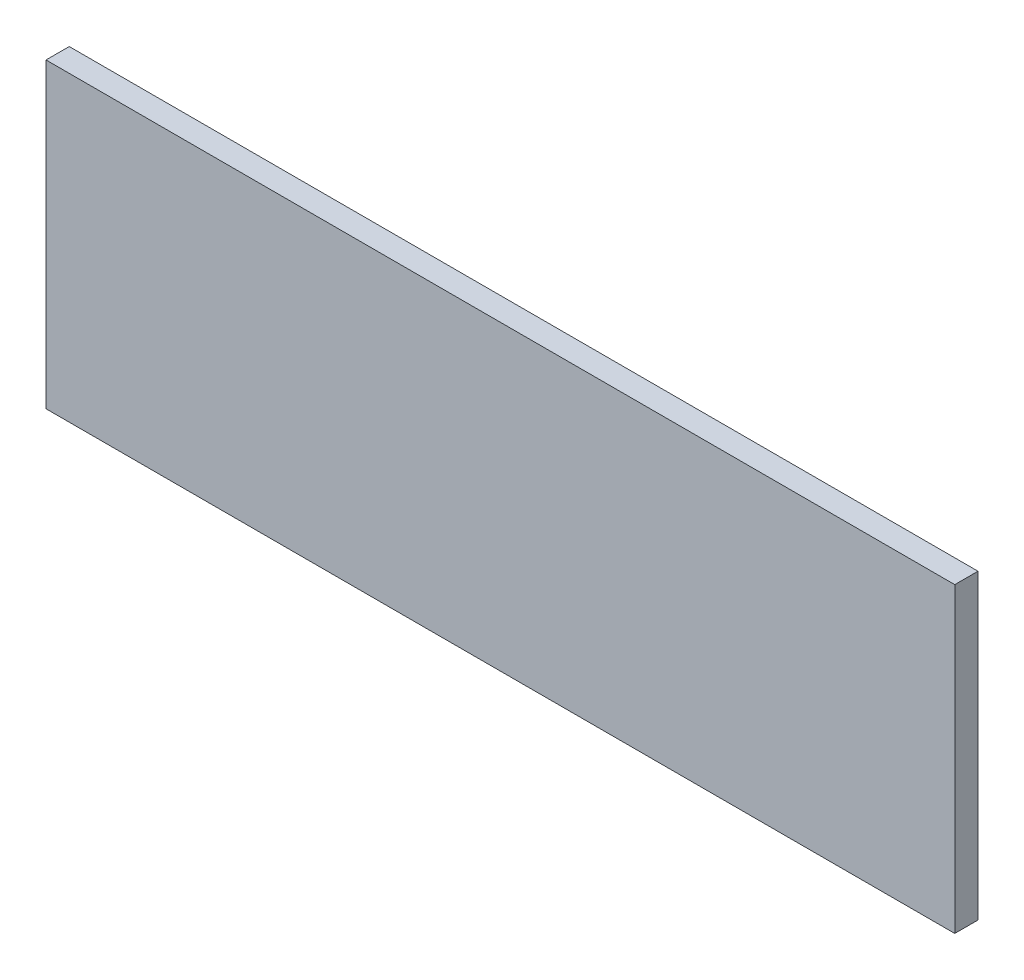
SolidWorks part; units mm, degrees
material "Custom Plastic"
ref_plane "X-Y Datum" through (0, 0, 0) normal (0, 0, 1) x (1, 0, 0)
ref_plane "X-Z Datum" through (0, 0, 0) normal (0, 1, 0) x (1, 0, 0)
ref_plane "Y-Z Datum" through (0, 0, 0) normal (1, 0, 0) x (0, 0, -1)
sketch "Sketch1" plane through (0, 0, 0) normal (0, 0, 1) x (1, 0, 0)
  line L1 (-39.12, -13.005) -> (39.12, -13.005)
  line L2 (-39.12, -13.005) -> (-39.12, 13.005)
  line L3 (-39.12, 13.005) -> (39.12, 13.005)
  line L4 (39.12, -13.005) -> (39.12, 13.005)
  line L5 (-39.12, -13.005) -> (39.12, 13.005) construction
  line L6 (-39.12, 13.005) -> (39.12, -13.005) construction
  point P0 (0, 0)
  dimension "D1" = 78.24
  dimension "D2" = 26.01
extrude "Boss-Extrude1" add sketch "Sketch1" along normal blind 2
